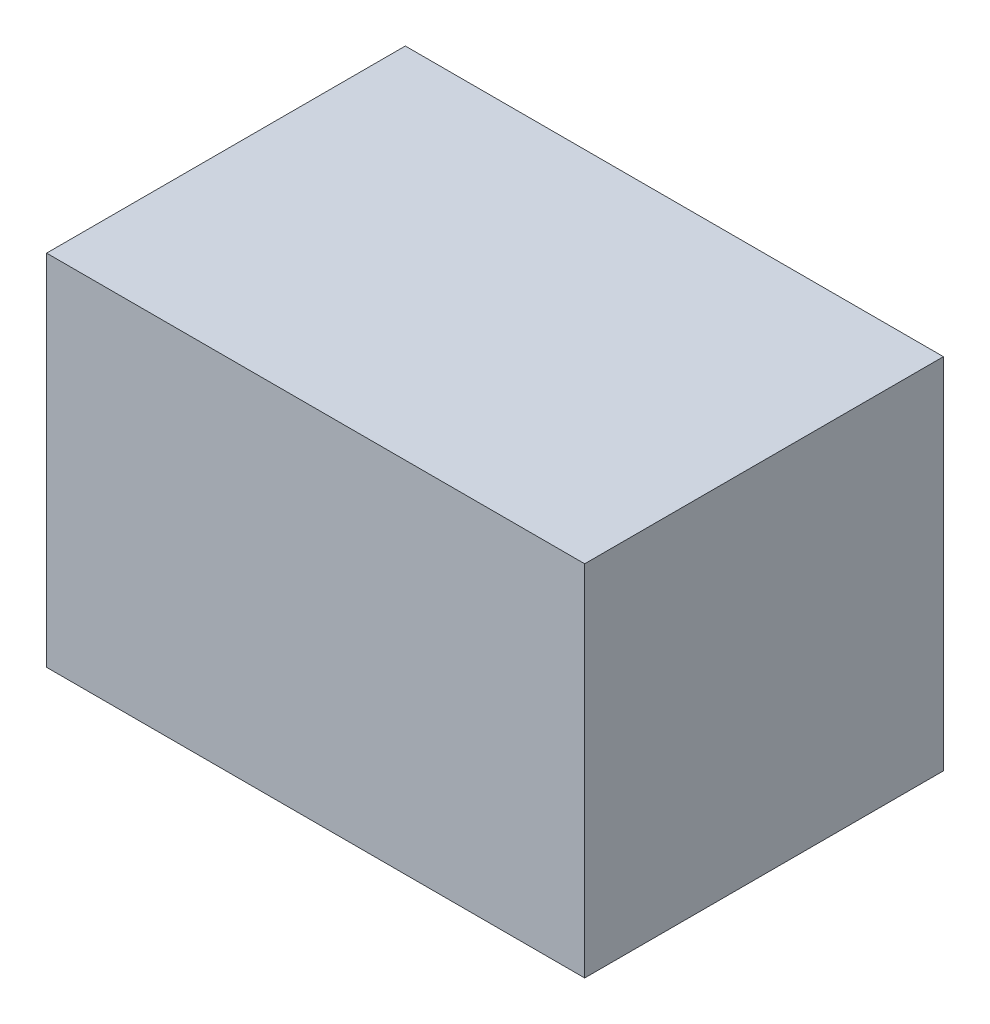
SolidWorks part; units mm, degrees
ref_plane "Ebene vorne" through (0, 0, 0) normal (0, 0, 1) x (1, 0, 0)
ref_plane "Ebene oben" through (0, 0, 0) normal (0, 1, 0) x (1, 0, 0)
ref_plane "Ebene rechts" through (0, 0, 0) normal (1, 0, 0) x (0, 0, -1)
sketch "Skizze2" plane through (0, 0, 0) normal (0, 1, 0) x (1, 0, 0)
  line L1 (67.5, -45) -> (-67.5, -45)
  line L2 (67.5, -45) -> (67.5, 45)
  line L3 (67.5, 45) -> (-67.5, 45)
  line L4 (-67.5, -45) -> (-67.5, 45)
  line L5 (67.5, -45) -> (-67.5, 45) construction
  line L6 (67.5, 45) -> (-67.5, -45) construction
  point P0 (0, 0)
  dimension "D1" = 90
  dimension "D2" = 135
extrude "Aufsatz-Linear austragen1" add sketch "Skizze2" along normal blind 90
